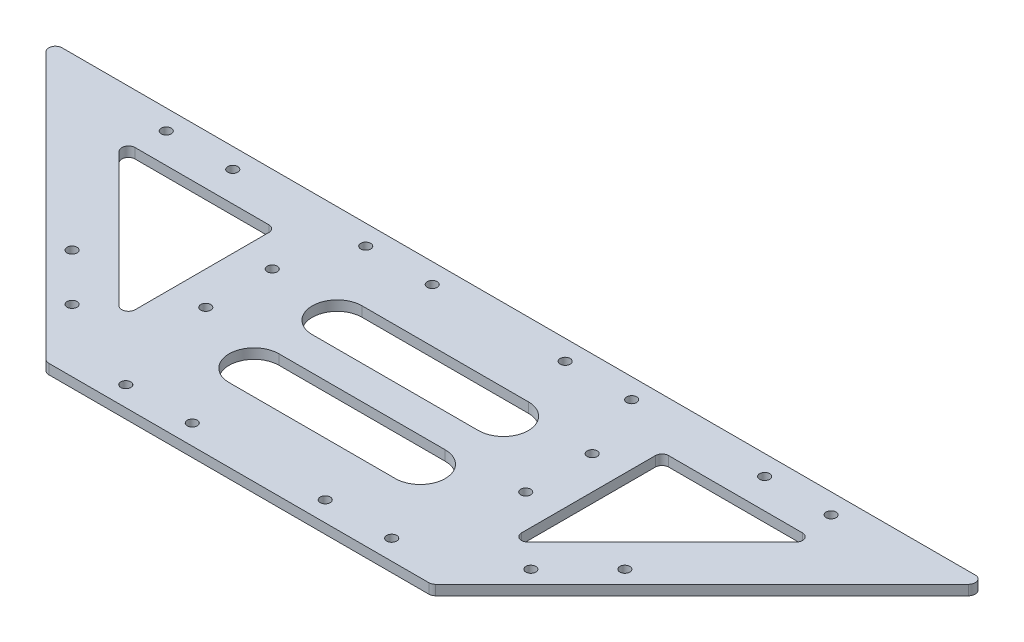
SolidWorks part; units mm, degrees
ref_plane "前视基准面" through (0, 0, 0) normal (0, 0, 1) x (1, 0, 0)
ref_plane "上视基准面" through (0, 0, 0) normal (0, 1, 0) x (1, 0, 0)
ref_plane "右视基准面" through (0, 0, 0) normal (1, 0, 0) x (0, 0, -1)
other "Configuration Table"
sketch "草图1" plane through (0, 0, 0) normal (0, 1, 0) x (1, 0, 0)
  line L0 (-40, 36.09) -> (-20, 36.09) construction
  line L1 (-58, 42.09) -> (58, 42.09)
  line L2 (-58, 42.09) -> (-58, -42.09)
  line L3 (-58, -42.09) -> (58, -42.09)
  line L4 (58, 42.09) -> (58, -42.09)
  line L5 (-58, 42.09) -> (58, -42.09) construction
  line L6 (-58, -42.09) -> (58, 42.09) construction
  line L7 (0, 0) -> (0, 42.09) construction
  line L8 (-48.125, 16.09) -> (-48.125, -3.91) construction
  line L9 (48.125, 16.09) -> (48.125, -3.91) construction
  line L10 (40, 36.09) -> (20, 36.09) construction
  line L11 (0, 0) -> (58, 0) construction
  line L12 (40, -36.09) -> (20, -36.09) construction
  line L13 (-40, -36.09) -> (-20, -36.09) construction
  circle A0 centre (-40, 36.09) radius 1.5
  circle A1 centre (-20, 36.09) radius 1.5
  circle A2 centre (-48.125, 16.09) radius 1.5
  circle A3 centre (-48.125, -3.91) radius 1.5
  circle A4 centre (48.125, -3.91) radius 1.5
  circle A5 centre (48.125, 16.09) radius 1.5
  circle A6 centre (20, 36.09) radius 1.5
  circle A7 centre (40, 36.09) radius 1.5
  circle A8 centre (40, -36.09) radius 1.5
  circle A9 centre (20, -36.09) radius 1.5
  circle A10 centre (-20, -36.09) radius 1.5
  circle A11 centre (-40, -36.09) radius 1.5
  point P0 (0, 0)
  dimension "D5" = 3
  dimension "D1" = 116
  dimension "D2" = 84.18
  dimension "D3" = 20
  dimension "D4" = 20
  dimension "D6" = 96.25
  dimension "D7" = 6
  dimension "D8" = 40
  dimension "D9" = 26
extrude "凸台-拉伸1" add sketch "草图1" along normal blind 3
sketch "草图2" plane through (0, 3, 0) normal (0, 1, 0) x (1, 0, 0)
  line L0 (-25, 12.5) -> (25, 12.5) construction
  line L1 (-25, 20) -> (25, 20)
  line L2 (-25, 5) -> (25, 5)
  line L3 (0, 0) -> (58, 0) construction
  line L4 (58, -42.09) -> (58, 42.09) construction
  line L5 (0, 0) -> (0, 12.5) construction
  line L6 (-25, -12.5) -> (25, -12.5) construction
  line L7 (-25, -20) -> (25, -20)
  line L8 (-25, -5) -> (25, -5)
  arc A0 (-25, 20) -> (-25, 5) centre (-25, 12.5) ccw
  arc A1 (25, 5) -> (25, 20) centre (25, 12.5) ccw
  arc A2 (-25, -20) -> (-25, -5) centre (-25, -12.5) cw
  arc A3 (25, -5) -> (25, -20) centre (25, -12.5) cw
  point P2 (0, 12.5)
  point P16 (0, -12.5)
  dimension "D1" = 7.5
  dimension "D2" = 10
  dimension "D3" = 50
extrude "切除-拉伸1" cut sketch "草图2" against normal blind 10
sketch "草图4" plane through (0, 3, 0) normal (0, 1, 0) x (1, 0, 0)
  line L0 (58, 42.09) -> (142.18, 42.09)
  line L1 (142.18, 42.09) -> (58, -42.09)
  line L2 (58, -42.09) -> (58, 42.09)
  line L3 (-58, -42.09) -> (-58, 42.09)
  line L4 (-58, 42.09) -> (-142.18, 42.09)
  line L5 (-142.18, 42.09) -> (-58, -42.09)
extrude "凸台-拉伸2" add sketch "草图4" against normal blind 3
sketch "草图10" plane through (0, 0, 0) normal (0, -1, 0) x (-1, 0, 0)
  line L0 (0, 42.09) -> (0, -42.09) construction
  line L1 (-142.18, 42.09) -> (142.18, 42.09) construction
  line L2 (58, -42.09) -> (-58, -42.09) construction
  circle A0 centre (69.0008, -23.249) radius 1.5
  circle A1 centre (83.143, -9.1069) radius 1.5
  circle A2 centre (-83.143, -9.1069) radius 1.5
  circle A3 centre (-69.0008, -23.249) radius 1.5
  dimension "D1" = 3
  dimension "D2" = 3
extrude "切除-拉伸2" cut sketch "草图10" against normal through all
sketch "草图11" plane through (0, 3, 0) normal (0, 1, 0) x (1, 0, 0)
  line L0 (-105.1977, 27.09) -> (-58.125, 27.09)
  line L1 (-58.125, 27.09) -> (-58.125, -19.9827)
  line L2 (-58.125, -19.9827) -> (-105.1977, 27.09)
  line L3 (0, 42.09) -> (0, -42.09) construction
  line L4 (142.18, 42.09) -> (-142.18, 42.09) construction
  line L5 (-58, -42.09) -> (58, -42.09) construction
  line L6 (-48.125, 16.09) -> (-48.125, -3.91) construction
  line L7 (-83.143, -9.1069) -> (-69.0008, -23.249) construction
  line L8 (83.143, -9.1069) -> (69.0008, -23.249) construction
  line L9 (48.125, 16.09) -> (48.125, -3.91) construction
  line L10 (58.125, -19.9827) -> (105.1977, 27.09)
  line L11 (58.125, 27.09) -> (58.125, -19.9827)
  line L12 (105.1977, 27.09) -> (58.125, 27.09)
  dimension "D1" = 10
  dimension "D2" = 15
  dimension "D3" = 10
extrude "切除-拉伸3" cut sketch "草图11" against normal through all
fillet "圆角2" radius 2 6 edges at (105.1977, 1.5, -27.09) (58.125, 1.5, 19.9827) (58.125, 1.5, -27.09) (-58.125, 1.5, -27.09) (-58.125, 1.5, 19.9827) (-105.1977, 1.5, -27.09)
fillet "圆角3" radius 2 4 edges at (-142.18, 1.5, -42.09) (142.18, 1.5, -42.09) (58, 1.5, 42.09) (-58, 1.5, 42.09)
sketch "草图12" plane through (0, 0, 0) normal (0, -1, 0) x (-1, 0, 0)
  line L0 (0, 39.0894) -> (0, -42.09) construction
  line L1 (57.1716, -42.09) -> (-57.1716, -42.09) construction
  circle A0 centre (-100, 36.0894) radius 1.5
  circle A1 centre (-80, 36.0894) radius 1.5
  circle A2 centre (80, 36.0894) radius 1.5
  circle A3 centre (100, 36.0894) radius 1.5
  dimension "D1" = 3
  dimension "D2" = 3
extrude "切除-拉伸4" cut sketch "草图12" against normal blind 10
